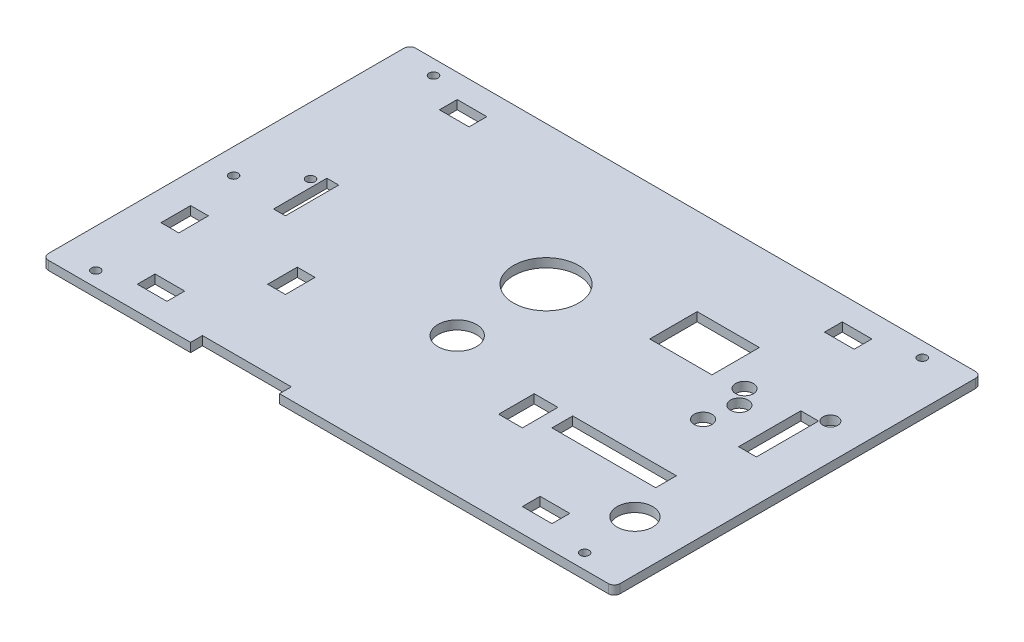
SolidWorks part; units mm, degrees
ref_plane "Front Plane" through (0, 0, 0) normal (0, 0, 1) x (1, 0, 0)
ref_plane "Top Plane" through (0, 0, 0) normal (0, 1, 0) x (1, 0, 0)
ref_plane "Right Plane" through (0, 0, 0) normal (1, 0, 0) x (0, 0, -1)
sketch "Sketch1" plane through (0, 0, 0) normal (0, 1, 0) x (1, 0, 0)
  line L1 (0, 0) -> (193, 0)
  line L2 (0, 0) -> (0, 124)
  line L3 (0, 124) -> (193, 124)
  line L4 (193, 0) -> (193, 124)
  circle A0 centre (13, 119) radius 1.5
  circle A1 centre (178, 119) radius 1.5
  circle A2 centre (13, 5) radius 1.5
  circle A3 centre (178, 5) radius 1.5
  dimension "D3" = 3
  dimension "D4" = 5
  dimension "D5" = 165
  dimension "D6" = 15
  dimension "D7" = 5
  dimension "D1" = 193
  dimension "D2" = 124
extrude "Boss-Extrude1" add sketch "Sketch1" along normal blind 3
sketch "Sketch2" plane through (0, 3, 0) normal (0, 1, 0) x (1, 0, 0)
  line L0 (193, 124) -> (0, 124) construction
  line L1 (136, 43) -> (171, 43)
  line L2 (136, 43) -> (136, 36)
  line L3 (136, 36) -> (171, 36)
  line L4 (171, 43) -> (171, 36)
  line L5 (126.5, 94.5) -> (147.5, 94.5)
  line L6 (126.5, 94.5) -> (126.5, 78.5)
  line L7 (126.5, 78.5) -> (147.5, 78.5)
  line L8 (147.5, 94.5) -> (147.5, 78.5)
  line L9 (173, 83) -> (179, 83)
  line L10 (173, 83) -> (173, 62)
  line L11 (173, 62) -> (179, 62)
  line L12 (179, 83) -> (179, 62)
  line L13 (123, 43) -> (131, 43)
  line L14 (123, 43) -> (123, 31)
  line L15 (123, 31) -> (131, 31)
  line L16 (131, 43) -> (131, 31)
  line L17 (193, 0) -> (193, 124) construction
  circle A0 centre (157, 80) radius 3
  circle A1 centre (161, 74.2554) radius 3
  circle A2 centre (159, 64) radius 3
  circle A3 centre (181, 85) radius 2.5
  circle A4 centre (176, 24) radius 6
  dimension "D1" = 12
  dimension "D5" = 12
  dimension "D8" = 5
  dimension "D11" = 6
  dimension "D14" = 7
  dimension "D15" = 4
  dimension "D16" = 2
  dimension "D17" = 16
  dimension "D18" = 22
  dimension "D20" = 1.5
  dimension "D27" = 12
  dimension "D2" = 8
  dimension "D3" = 35
  dimension "D4" = 7
  dimension "D6" = 21
  dimension "D7" = 6
  dimension "D9" = 16
  dimension "D10" = 21
  dimension "D12" = 2
  dimension "D13" = 2
  dimension "D19" = 9.5
  dimension "D21" = 12
  dimension "D22" = 5
  dimension "D23" = 5
  dimension "D24" = 35.5
  dimension "D25" = 19
  dimension "D26" = 29.5
  dimension "D28" = 3.5
extrude "Cut-Extrude1" cut sketch "Sketch2" against normal through all
sketch "Sketch3" plane through (0, 3, 0) normal (0, 1, 0) x (1, 0, 0)
  line L0 (193, 124) -> (0, 124) construction
  line L1 (193, 0) -> (193, 124) construction
  circle A0 centre (93, 77) radius 11
  circle A1 centre (93, 47) radius 6.5
  point P9 (193, 62)
  dimension "D1" = 22
  dimension "D2" = 13
  dimension "D3" = 30
  dimension "D4" = 47
  dimension "D5" = 100
extrude "Cut-Extrude2" cut sketch "Sketch3" against normal through all
sketch "Sketch4" plane through (0, 3, 0) normal (0, 1, 0) x (1, 0, 0)
  line L0 (193, 124) -> (0, 124) construction
  line L1 (24, 116) -> (34, 116)
  line L2 (24, 116) -> (24, 110)
  line L3 (24, 110) -> (34, 110)
  line L4 (34, 116) -> (34, 110)
  line L5 (154, 116) -> (164, 116)
  line L6 (154, 116) -> (154, 110)
  line L7 (154, 110) -> (164, 110)
  line L8 (164, 116) -> (164, 110)
  line L9 (24, 14) -> (34, 14)
  line L10 (24, 14) -> (24, 8)
  line L11 (24, 8) -> (34, 8)
  line L12 (34, 14) -> (34, 8)
  line L13 (154, 14) -> (164, 14)
  line L14 (154, 14) -> (154, 8)
  line L15 (154, 8) -> (164, 8)
  line L16 (164, 14) -> (164, 8)
  line L17 (0, 124) -> (0, 0) construction
  line L18 (0, 0) -> (193, 0) construction
  dimension "D1" = 10
  dimension "D2" = 6
  dimension "D3" = 8
  dimension "D4" = 24
  dimension "D5" = 120
  dimension "D6" = 8
extrude "Cut-Extrude3" cut sketch "Sketch4" against normal through all
sketch "Sketch5" plane through (0, 3, 0) normal (0, 1, 0) x (1, 0, 0)
  line L0 (0, 0) -> (193, 0) construction
  line L1 (50, 0) -> (80, 0)
  line L2 (50, 0) -> (50, 4)
  line L3 (50, 4) -> (80, 4)
  line L4 (80, 0) -> (80, 4)
  line L5 (0, 124) -> (0, 0) construction
  dimension "D1" = 4
  dimension "D2" = 30
  dimension "D3" = 50
extrude "Cut-Extrude4" cut sketch "Sketch5" against normal through all
sketch "Sketch6" plane through (0, 3, 0) normal (0, 1, 0) x (1, 0, 0)
  line L0 (193, 124) -> (0, 124) construction
  line L1 (25, 71) -> (29, 71)
  line L2 (25, 71) -> (25, 53)
  line L3 (25, 53) -> (29, 53)
  line L4 (29, 71) -> (29, 53)
  line L5 (0, 124) -> (0, 0) construction
  circle A0 centre (8.5, 56) radius 1.5
  circle A1 centre (22.5, 68) radius 1.5
  dimension "D1" = 3
  dimension "D2" = 3
  dimension "D3" = 14
  dimension "D6" = 3
  dimension "D9" = 2.5
  dimension "D4" = 4
  dimension "D5" = 18
  dimension "D7" = 53
  dimension "D8" = 25
extrude "Cut-Extrude5" cut sketch "Sketch6" against normal through all
sketch "Sketch7" plane through (0, 3, 0) normal (0, 1, 0) x (1, 0, 0)
  line L0 (0, 0) -> (50, 0) construction
  line L1 (10, 40) -> (16, 40)
  line L2 (10, 40) -> (10, 30)
  line L3 (10, 30) -> (16, 30)
  line L4 (16, 40) -> (16, 30)
  line L5 (46, 40) -> (52, 40)
  line L6 (46, 40) -> (46, 30)
  line L7 (46, 30) -> (52, 30)
  line L8 (52, 40) -> (52, 30)
  line L9 (0, 124) -> (0, 0) construction
  dimension "D1" = 30
  dimension "D2" = 6
  dimension "D3" = 10
  dimension "D4" = 30
  dimension "D5" = 10
extrude "Cut-Extrude6" cut sketch "Sketch7" against normal through all
fillet "Fillet1" radius 2 4 edges at (193, 1.5, 0) (193, 1.5, -124) (0, 1.5, 0) (0, 1.5, -124)
